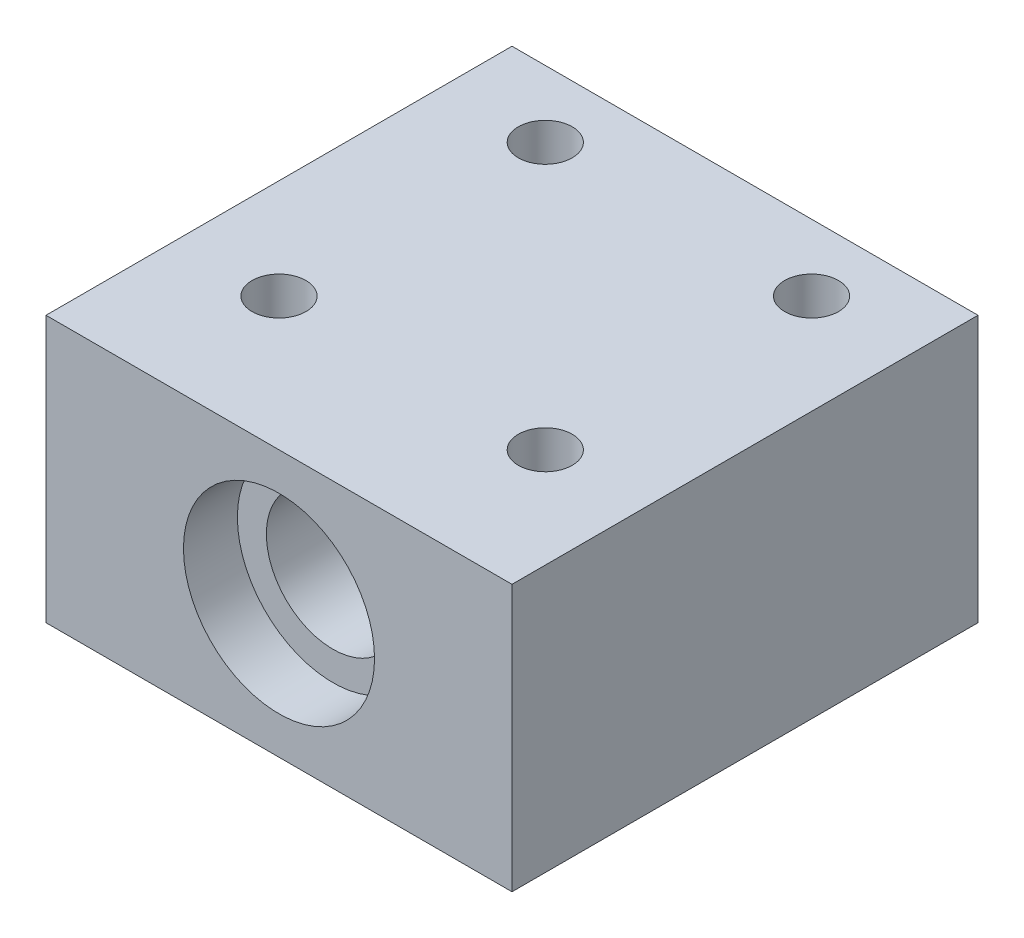
SolidWorks part; units mm, degrees
ref_plane "Front Plane" through (0, 0, 0) normal (0, 0, 1) x (1, 0, 0)
ref_plane "Top Plane" through (0, 0, 0) normal (0, 1, 0) x (1, 0, 0)
ref_plane "Right Plane" through (0, 0, 0) normal (1, 0, 0) x (0, 0, -1)
sketch "Sketch1" plane through (0, 0, 0) normal (0, 0, 1) x (1, 0, 0)
  line L0 (0, 0) -> (0, -20) construction
  line L1 (-35, 20) -> (35, 20)
  line L2 (-35, 20) -> (-35, -20)
  line L3 (-35, -20) -> (35, -20)
  line L4 (35, 20) -> (35, -20)
  circle A0 centre (0, 0) radius 10
  circle A1 centre (0, 0) radius 14.2875 construction
  dimension "D1" = 20
  dimension "D2" = 20
  dimension "D5" = 28.575
  dimension "D3" = 20
  dimension "D4" = 70
extrude "Boss-Extrude1" add sketch "Sketch1" against normal blind 30 and the other way blind 40
sketch "Sketch2" plane through (0, 0, 0) normal (0, 1, 0) x (1, 0, 0)
  line L0 (0, 0) -> (0, 20) construction
  line L2 (-20, 20) -> (20, 20) construction
  line L3 (20, -20) -> (-20, -20) construction
  line L4 (20, -20) -> (20, 20) construction
  line L5 (20, 20) -> (-20, 20) construction
  line L6 (-20, -20) -> (-20, 20) construction
  line L7 (20, -20) -> (-20, 20) construction
  line L8 (20, 20) -> (-20, -20) construction
  circle A0 centre (-20, 20) radius 4.05
  circle A1 centre (20, 20) radius 4.05
  circle A2 centre (0, 5) radius 2.5 construction
  circle A3 centre (-20, -20) radius 4.05
  circle A4 centre (20, -20) radius 4.05
  dimension "D1" = 8.1
  dimension "D4" = 5
  dimension "D5" = 5
  dimension "D3" = 40
extrude "Cut-Extrude1" cut sketch "Sketch2" against normal blind 25 and the other way blind 25
sketch "Sketch3" plane through (0, 0, 0) normal (0, 0, 1) x (1, 0, 0)
  line L0 (-25, 0) -> (25, 0) construction
  circle A0 centre (0, 0) radius 14.35
  dimension "D1" = 28.7
  dimension "D3" = 25
extrude "Cut-Extrude2" cut sketch "Sketch3" against normal blind 8.1 from surface at 40 starting at face at (0, 0, 40)
sketch "Sketch4" plane through (0, 0, 0) normal (0, 0, 1) x (1, 0, 0)
  circle A0 centre (0, 0) radius 14.2875
  dimension "D1" = 28.575
extrude "Cut-Extrude3" cut sketch "Sketch4" along normal blind 8.1 from surface at -30 starting at face at (10, 0, -30)
